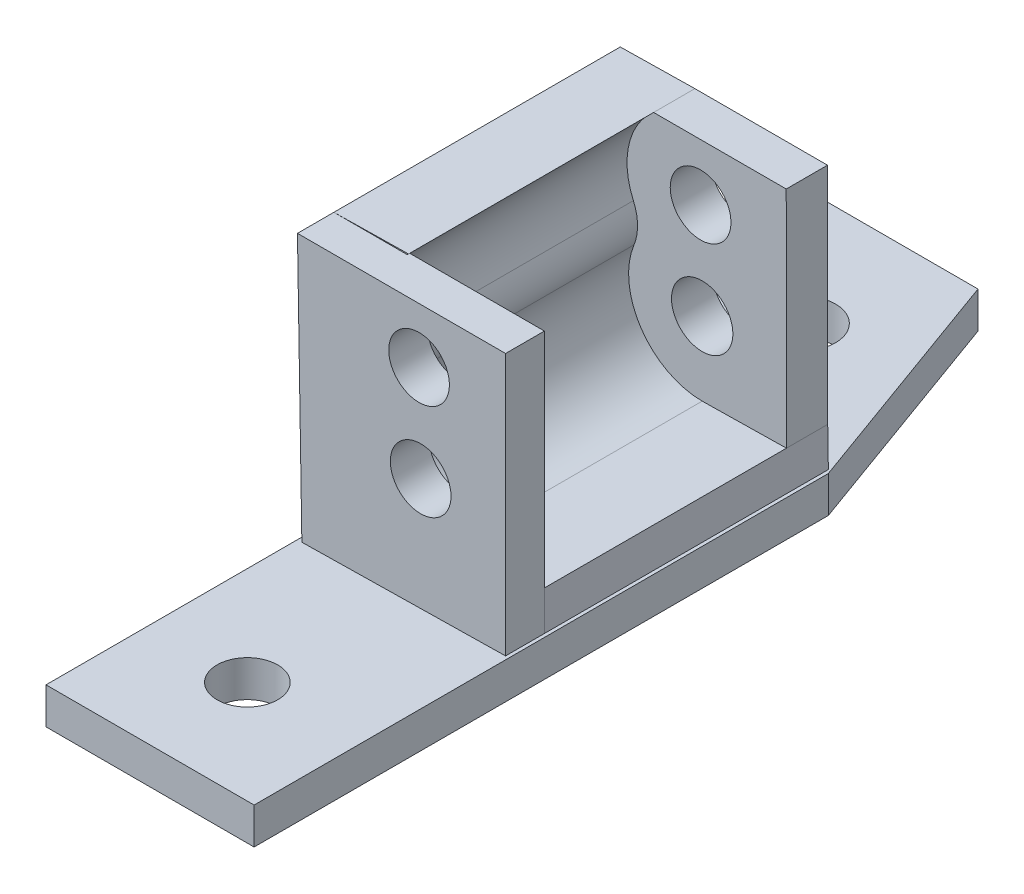
SolidWorks part; units mm, degrees
ref_plane "Front Plane" through (0, 0, 0) normal (0, 0, 1) x (1, 0, 0)
ref_plane "Top Plane" through (0, 0, 0) normal (0, 1, 0) x (1, 0, 0)
ref_plane "Right Plane" through (0, 0, 0) normal (1, 0, 0) x (0, 0, -1)
sketch "Sketch1" plane through (0, 0, 0) normal (0, 0, 1) x (1, 0, 0)
  line L0 (-428.7396, 136.6501) -> (-428.2778, 108.8815)
  line L1 (-428.2778, 108.8815) -> (-449.5961, 108.527)
  line L2 (-428.7396, 136.6501) -> (-450.0578, 136.2956)
  line L3 (-450.0578, 136.2956) -> (-449.5961, 108.527)
  line L4 (-437.1648, 112.7993) -> (-428.3454, 112.9449)
  line L5 (-414.2767, 113.1788) -> (-437.0368, 112.8004) construction
  arc A0 (-442.1947, 136.4669) -> (-444.3649, 127.3721) centre (-437.3311, 130.5) ccw
  arc A1 (-444.2998, 123.3969) -> (-444.3649, 127.3721) centre (-449.0067, 125.308) ccw construction
  arc A2 (-443.5981, 134.9701) -> (-444.3649, 127.3721) centre (-437.3311, 130.5) ccw construction
  arc A3 (-444.3649, 127.3721) -> (-444.2998, 123.3969) centre (-449.0067, 125.308) cw
  arc A4 (-444.2998, 123.3969) -> (-437.1648, 112.7993) centre (-437.1648, 120.5) ccw
  arc A5 (-443.2811, 115.8212) -> (-437.0368, 112.8004) centre (-437.1648, 120.5) ccw construction
  dimension "D1" = 6.4368
  dimension "D2" = 4.064
extrude "Boss-Extrude1" add sketch "Sketch1" against normal blind 29.972 contours A4 A3 A0 L2 L3 L1 L0 L4
sketch "Sketch4" plane through (0, 0, 0) normal (0, 0, 1) x (1, 0, 0)
  line L0 (-450.0578, 136.2956) -> (-449.5961, 108.527)
  line L1 (-449.5961, 108.527) -> (-428.2778, 108.8815)
  line L2 (-450.0578, 136.2956) -> (-428.2778, 136.2956)
  line L3 (-428.2778, 136.2956) -> (-428.2778, 108.8815)
  circle A0 centre (-437.1648, 120.5) radius 3.175
  circle A1 centre (-437.3311, 130.5) radius 3.175
extrude "Boss-Extrude2" add sketch "Sketch4" along normal blind 3.81 and the other way blind 0.254
sketch "Sketch6" plane through (0, 0, -29.972) normal (0, 0, -1) x (-1, 0, 0)
  line L0 (442.245, 136.4255) -> (428.3677, 136.4255)
  line L1 (428.3677, 136.4255) -> (428.3454, 112.9449)
  line L2 (437.1648, 112.7993) -> (428.3454, 112.9449)
  arc A0 (442.245, 136.4255) -> (444.3649, 127.3721) centre (437.3311, 130.5) cw
  arc A1 (444.3649, 127.3721) -> (444.2998, 123.3969) centre (449.0067, 125.308) ccw
  arc A2 (444.2998, 123.3969) -> (437.1648, 112.7993) centre (437.1648, 120.5) cw
  circle A3 centre (437.3311, 130.5) radius 3.1778
  circle A4 centre (437.1648, 120.5) radius 3.2088
extrude "Boss-Extrude3" add sketch "Sketch6" against normal blind 4.318
ref_plane "Plane1" through (0.0131, 108.4727, 0) normal (0.0001, 1, 0) x (1, -0.0001, 0)
sketch "Sketch7" plane through (0.0131, 108.4727, 0) normal (0.0001, 1, 0) x (1, -0.0001, 0)
  line L0 (-428.2943, -3.81) -> (-428.2943, -30.1229)
  line L1 (-428.2943, -30.1229) -> (-450.0743, -30.1229)
  line L2 (-450.0743, -30.1229) -> (-450.0743, -3.81)
  line L3 (-450.0743, -3.81) -> (-450.0743, 29.972)
  line L4 (-450.0743, 29.972) -> (-460.1428, 54.5228)
  line L5 (-460.1428, 54.5228) -> (-437.1806, 54.5228)
  line L6 (-437.1806, 54.5228) -> (-428.2943, 29.972)
  line L7 (-428.2943, 29.972) -> (-428.2943, -3.81)
  line L8 (-450.0743, 29.972) -> (-450.0743, -3.81)
  circle A0 centre (-443.2867, 42.1855) radius 3.523
  circle A1 centre (-439.7637, -19.3592) radius 3.1713
extrude "Boss-Extrude4" add sketch "Sketch7" against normal blind 3.81 separate body contours L7 L6 L5 L4 L3 L2 L1 L0 A1 A0
